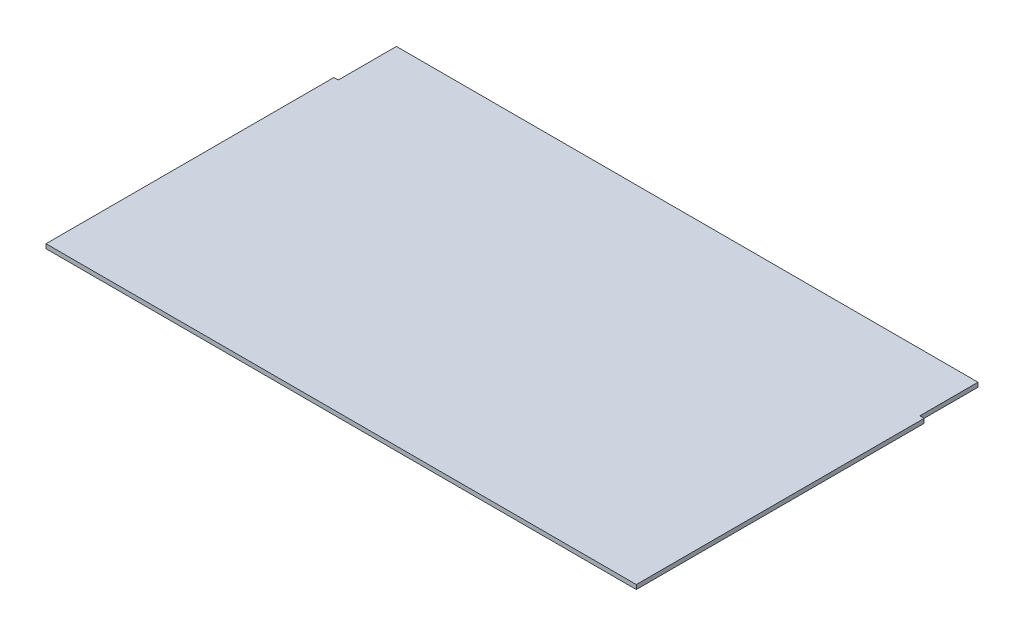
SolidWorks part; units mm, degrees
material "Acrylic (Medium-high impact)"
ref_plane "Front Plane" through (0, 0, 0) normal (0, 0, 1) x (1, 0, 0)
ref_plane "Top Plane" through (0, 0, 0) normal (0, 1, 0) x (1, 0, 0)
ref_plane "Right Plane" through (0, 0, 0) normal (1, 0, 0) x (0, 0, -1)
sketch "Sketch1" plane through (0, 0, 0) normal (0, 1, 0) x (1, 0, 0)
  line L1 (-203, -99) -> (203, -99)
  line L2 (-203, -99) -> (-203, 99)
  line L3 (-203, 99) -> (203, 99)
  line L4 (203, -99) -> (203, 99)
  line L5 (-203, -99) -> (203, 99) construction
  line L6 (-203, 99) -> (203, -99) construction
  point P0 (0, 0)
  dimension "D1" = 198
  dimension "D2" = 406
extrude "Boss-Extrude1" add sketch "Sketch1" along normal blind 3
sketch "Sketch2" plane through (0, 3, 0) normal (0, 1, 0) x (1, 0, 0)
  line L0 (0, -1000) -> (0, 49000) construction
  line L1 (203, 99) -> (-203, 99) construction
  line L2 (-200, 99) -> (200, 99)
  line L3 (-200, 99) -> (-200, 139)
  line L4 (-200, 139) -> (200, 139)
  line L5 (200, 99) -> (200, 139)
  line L6 (203, -99) -> (203, 99) construction
  point P9 (0, 139)
  dimension "D1" = 3
  dimension "D2" = 40
extrude "Boss-Extrude2" add sketch "Sketch2" against normal up to surface (3 mm away) up to face at (0, 0, 0)
